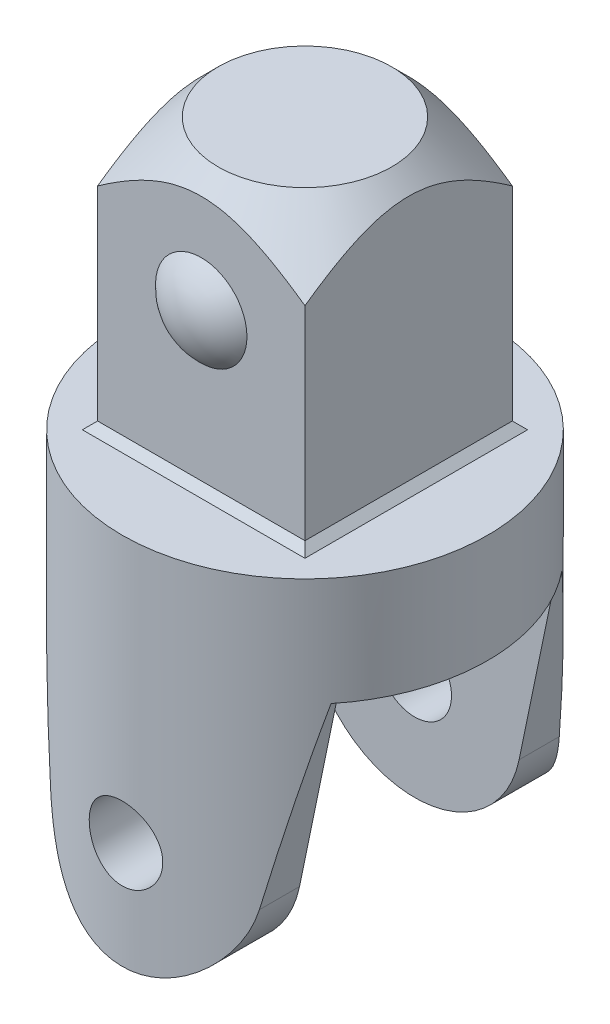
SolidWorks part; units mm, degrees
ref_plane "Front Plane" through (0, 0, 0) normal (0, 0, 1) x (1, 0, 0)
ref_plane "Top Plane" through (0, 0, 0) normal (0, 1, 0) x (1, 0, 0)
ref_plane "Right Plane" through (0, 0, 0) normal (1, 0, 0) x (0, 0, -1)
sketch "Sketch1" plane through (0, 0, 0) normal (0, 1, 0) x (1, 0, 0)
  circle A0 centre (0, 0) radius 12
  dimension "D1" = 24
extrude "Boss-Extrude1" add sketch "Sketch1" along normal blind 33.53
sketch "Sketch2" plane through (0, 33.53, 0) normal (0, 1, 0) x (1, 0, 0)
  line L0 (-6.5, 6.5) -> (-2.5, 6.5)
  line L1 (-6.5, 6.5) -> (6.5, 6.5) construction
  line L2 (-6.5, 6.5) -> (-6.5, -6.5) construction
  line L3 (-6.5, -6.5) -> (6.5, -6.5) construction
  line L4 (6.5, 6.5) -> (6.5, -6.5) construction
  line L5 (-6.5, 6.5) -> (6.5, -6.5) construction
  line L6 (-6.5, -6.5) -> (6.5, 6.5) construction
  line L7 (2.5, 6.5) -> (6.5, 6.5)
  line L8 (6.5, 6.5) -> (6.5, 2.5)
  line L9 (6.5, -2.5) -> (6.5, -6.5)
  line L10 (6.5, -6.5) -> (2.5, -6.5)
  line L11 (-2.5, -6.5) -> (-6.5, -6.5)
  line L12 (-6.5, -6.5) -> (-6.5, -2.5)
  line L13 (-6.5, 2.5) -> (-6.5, 6.5)
  arc A0 (-2.5, 6.5) -> (2.5, 6.5) centre (0, 2.4611) cw
  arc A1 (6.5, 2.5) -> (6.5, -2.5) centre (2.4611, 0) cw
  arc A2 (2.5, -6.5) -> (-2.5, -6.5) centre (0, -2.4611) cw
  arc A3 (-6.5, -2.5) -> (-6.5, 2.5) centre (-2.4611, 0) cw
  point P0 (0, 0)
  point P9 (0, 7.2111)
  point P28 (0, 0)
  dimension "D3" = 4.75
  dimension "D1" = 13
  dimension "D2" = 4
  dimension "D4" = 4
extrude "Cut-Extrude1" cut sketch "Sketch2" against normal blind 19.6
chamfer "Chamfer1" distance 0.4 angle 45 4 edges at (-6.5, 23.73, 6.5) (6.5, 23.73, 6.5) (-6.5, 23.73, -6.5) (6.5, 23.73, -6.5)
sketch "Sketch3" plane through (0, 33.53, 0) normal (0, 1, 0) x (1, 0, 0)
  circle A0 centre (0, 0) radius 9.375
  dimension "D1" = 18.75
extrude "Cut-Extrude2" cut sketch "Sketch3" against normal blind 3.4 draft 35
sketch "Sketch4" plane through (0, 0, 0) normal (0, -1, 0) x (1, 0, 0)
  line L1 (-12, 7.2111) -> (12, 7.2111)
  line L2 (-12, 7.2111) -> (-12, -7.2111)
  line L3 (-12, -7.2111) -> (12, -7.2111)
  line L4 (12, 7.2111) -> (12, -7.2111)
  arc A0 (2.5, 6.5) -> (-2.5, 6.5) centre (0, 2.4611) ccw construction
  arc A1 (-2.5, -6.5) -> (2.5, -6.5) centre (0, -2.4611) ccw construction
  circle A2 centre (0, 0) radius 12 construction
extrude "Cut-Extrude3" cut sketch "Sketch4" against normal blind 17.4
sketch "Sketch5" plane through (0, 0, 0) normal (0, 0, 1) x (1, 0, 0)
  line L0 (12, 17.4) -> (9.3, 17.4)
  line L1 (9.3, 17.4) -> (6.8548, 5.5817)
  line L2 (0, 0) -> (0, 33.53) construction
  line L3 (12, 33.53) -> (-12, 33.53) construction
  line L4 (-12, 17.4) -> (-9.3, 17.4)
  line L5 (-9.3, 17.4) -> (-6.8548, 5.5817)
  line L6 (-6.8548, 5.5817) -> (6.8548, 5.5817) construction
  line L7 (-12, 17.4) -> (-12, -3.1923)
  line L8 (-12, -3.1923) -> (12, -3.1923)
  line L9 (12, -3.1923) -> (12, 17.4)
  arc A0 (-6.8548, 5.5817) -> (6.8548, 5.5817) centre (0, 7) ccw
  circle A1 centre (0, 7) radius 2.415
  dimension "D1" = 7
  dimension "D3" = 4.83
  dimension "D2" = 2.7
extrude "Cut-Extrude4" cut sketch "Sketch5" against normal mid plane 67.4 contours A1 | A0 L5 L4 L7 L8 L9 L0 L1
sketch "Sketch6" plane through (0, 33.53, 0) normal (0, 1, 0) x (1, 0, 0)
  circle A0 centre (0, 0) radius 12
extrude "Cut-Extrude5" cut sketch "Sketch6" against normal blind 9
sketch "Sketch7" plane through (0, 24.53, 0) normal (0, 1, 0) x (1, 0, 0)
  circle A1 centre (0, 0) radius 12
  circle A2 centre (0, 0) radius 12
  dimension "D1" = 0
extrude "Boss-Extrude2" add sketch "Sketch7" against normal up to surface (7.13 mm away) up to face at (5.9936, 17.4, 0)
sketch "Sketch8" plane through (0, 24.53, 0) normal (0, 1, 0) x (1, 0, 0)
  line L1 (-6.81, 6.81) -> (6.81, 6.81)
  line L2 (-6.81, 6.81) -> (-6.81, -6.81)
  line L3 (-6.81, -6.81) -> (6.81, -6.81)
  line L4 (6.81, 6.81) -> (6.81, -6.81)
  line L5 (-6.81, 6.81) -> (6.81, -6.81) construction
  line L6 (-6.81, -6.81) -> (6.81, 6.81) construction
  point P0 (0, 0)
  dimension "D1" = 13.62
extrude "Boss-Extrude3" add sketch "Sketch8" along normal blind 17.8
ref_axis "Axis1" through (0, 44.4465, 0) along (0, -1, 0)
sketch "Sketch9" plane through (0, 0, 0) normal (0, 0, 1) x (1, 0, 0)
  line L0 (5.7, 42.33) -> (13.1113, 42.33)
  line L1 (-6.81, 42.33) -> (6.81, 42.33) construction
  line L2 (13.1113, 42.33) -> (13.1113, 34.9187)
  line L3 (13.1113, 34.9187) -> (5.7, 42.33)
  line L4 (0, 44.4465) -> (0, -2.1165) construction
  dimension "D1" = 45
  dimension "D2" = 5.7
revolve "Cut-Revolve1" cut sketch "Sketch9" angle 360 about axis through (0, 44.4465, 0) along (0, -1, 0)
chamfer "Chamfer2" distance 0.5 angle 45 4 edges at (0, 24.53, -6.81) (6.81, 24.53, 0) (-6.81, 24.53, 0) (0, 24.53, 6.81)
sketch "Sketch10" plane through (0, 0, 0) normal (1, 0, 0) x (0, 0, -1)
  line L0 (6.81, 34.73) -> (6.81, 31.73)
  line L1 (6.81, 38.3992) -> (6.81, 25.03) construction
  line L2 (6.81, 34.73) -> (8.16, 34.73) construction
  line L3 (5.7, 42.33) -> (-5.7, 42.33) construction
  line L4 (6.81, 34.73) -> (8.16, 34.73)
  arc A0 (8.16, 34.73) -> (6.81, 31.73) centre (4.1517, 34.73) cw
  dimension "D1" = 7.6
  dimension "D2" = 3
  dimension "D3" = 1.35
revolve "Revolve1" add sketch "Sketch10" angle 360 about L2
mirror "Mirror1" about plane through (0, 0, 0) normal (0, 0, 1) of "Revolve1"
scale "Scale1" scale about centroid uniform scaling yes scale factor 0.49
